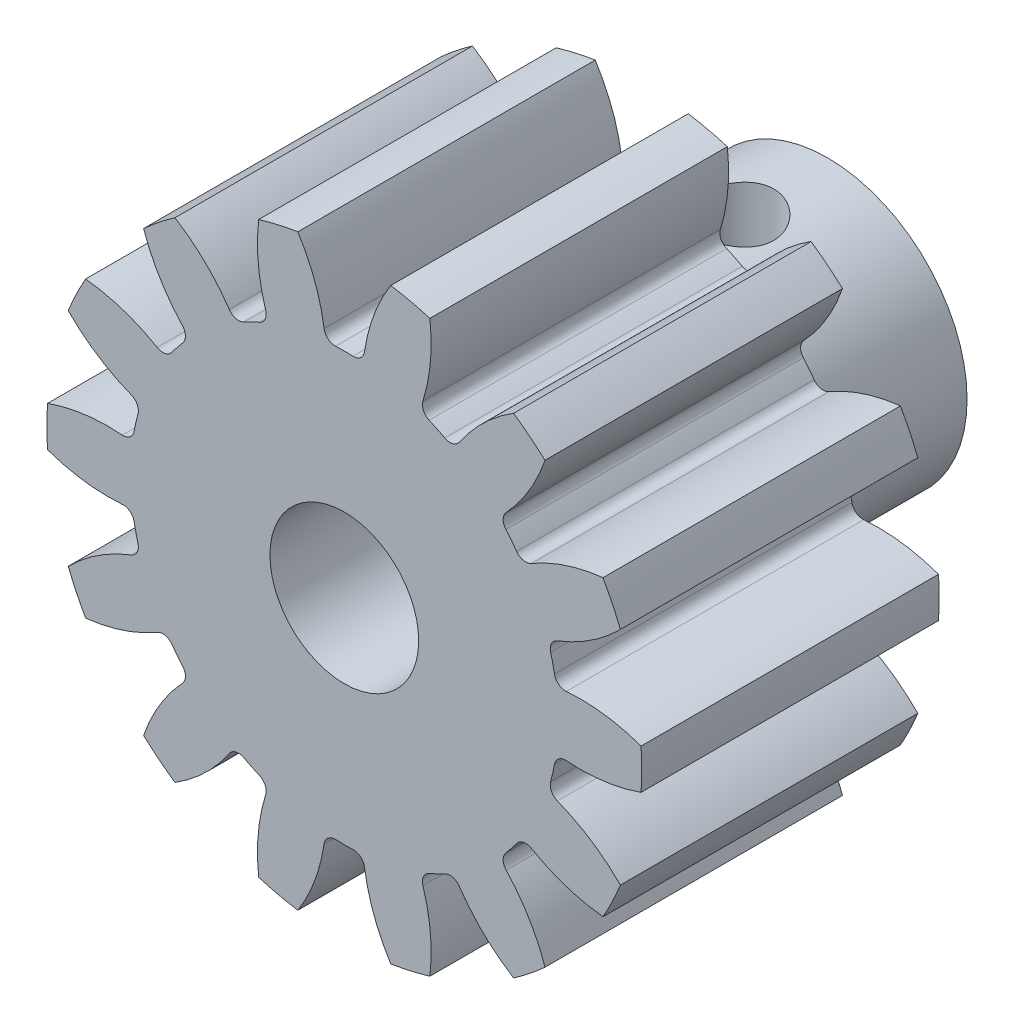
SolidWorks part; units mm, degrees
ref_plane "Ön Düzlem" through (0, 0, 0) normal (0, 0, 1) x (1, 0, 0)
ref_plane "Üst Düzlem" through (0, 0, 0) normal (0, 1, 0) x (1, 0, 0)
ref_plane "Sağ Düzlem" through (0, 0, 0) normal (1, 0, 0) x (0, 0, -1)
sketch "Çizim1" plane through (0, 0, 0) normal (0, 0, 1) x (1, 0, 0)
  circle A0 centre (0, 0) radius 14
  circle A1 centre (0, 0) radius 16
  circle A2 centre (0, 0) radius 11.5
  dimension "D1" = 28
  dimension "D2" = 32
  dimension "D3" = 23
extrude "Yükseklik-Ekstrüzyon1" add sketch "Çizim1" along normal mid plane 16 contours A1
sketch "Çizim2" plane through (0, 0, 8) normal (0, 0, 1) x (1, 0, 0)
  line L0 (0, 0) -> (0, 16) construction
  line L1 (-1.5675, 13.912) -> (1.5675, 13.912) construction
  line L2 (0, 9.6053) -> (-2.6177, 16.7973) construction
  line L3 (0, 0) -> (-1.0207, 11.4546) construction
  line L4 (0, 0) -> (3.5603, 15.5988) construction
  line L5 (1.5675, 13.912) -> (4.6239, 13.2144) construction
  circle A0 centre (0, 0) radius 16 construction
  arc A1 (-3.1496, 16.7057) -> (-1.0207, 11.4546) centre (-10.685, 10.5935) cw
  arc A2 (3.1496, 16.7057) -> (1.0207, 11.4546) centre (10.685, 10.5935) ccw
  circle A3 centre (0, 0) radius 11.5 construction
  arc A4 (1.0207, 11.4546) -> (-1.0207, 11.4546) centre (0, 0) ccw
  circle A5 centre (0, 0) radius 14 construction
  circle A6 centre (0, 0) radius 16 construction
  circle A7 centre (0, 0) radius 17
  arc A8 (3.1496, 16.7057) -> (-3.1496, 16.7057) centre (0, 0) ccw
  dimension "D2" = 20
  dimension "D3" = 12.857
  dimension "D1" = 1
extrude "Kes-Ekstrüzyon1" cut sketch "Çizim2" against normal blind 16
fillet "Radyus1" radius 0.6 2 edges at (1.0207, 11.4546, 0) (-1.0207, 11.4546, 0)
pattern_circular "Dairesel Kaplama1" count 14 over 360 about axis through (0, 0, 0) along (0, 0, 1) of "Radyus1", "Kes-Ekstrüzyon1"
sketch "Sketch1" plane through (0, 0, -8) normal (0, 0, -1) x (-1, 0, 0)
  circle A0 centre (0, 0) radius 4
  dimension "D1" = 8
extrude "Cut-Extrude1" cut sketch "Sketch1" against normal blind 26
sketch "Sketch2" plane through (0, 0, -8) normal (0, 0, -1) x (-1, 0, 0)
  circle A0 centre (0, 0) radius 4
  circle A1 centre (0, 0) radius 7.5
  dimension "D1" = 8
  dimension "D2" = 15
extrude "Boss-Extrude1" add sketch "Sketch2" along normal blind 10
sketch "Sketch3" plane through (0, 0, 0) normal (0, 1, 0) x (1, 0, 0)
  line L0 (0, 0) -> (0, 18) construction
  line L1 (4, 18) -> (-4, 18) construction
  line L2 (7.5, 18) -> (-7.5, 18) construction
  circle A0 centre (0, 13) radius 2.1
  dimension "D1" = 4.2
  dimension "D2" = 5
extrude "Cut-Extrude2" cut sketch "Sketch3" against normal through all both and the other way through all
equation "\"m\"= 2mm'modül"
equation "\"z\"= 14'diş sayısı"
equation "\"D1@Çizim1\"=\"m\"*\"z\""
equation "\"D2@Çizim1\"=\"m\"*(\"z\"+2)"
equation "\"D3@Çizim1\"=\"m\"*(\"z\"-2.5)"
equation "\"D1@Yükseklik-Ekstrüzyon1\"=\"m\"*8"
equation "\"D3@Çizim2\"=180/\"z\""
equation "\"D1\"= \"m\" * 8"
equation "\"D1@Radyus1\"=\"m\"*0.3"
equation "\"D1@Dairesel Kaplama1\"=\"z\""
equation "\"D1@Kes-Ekstrüzyon1\"=\"m\"*8"
